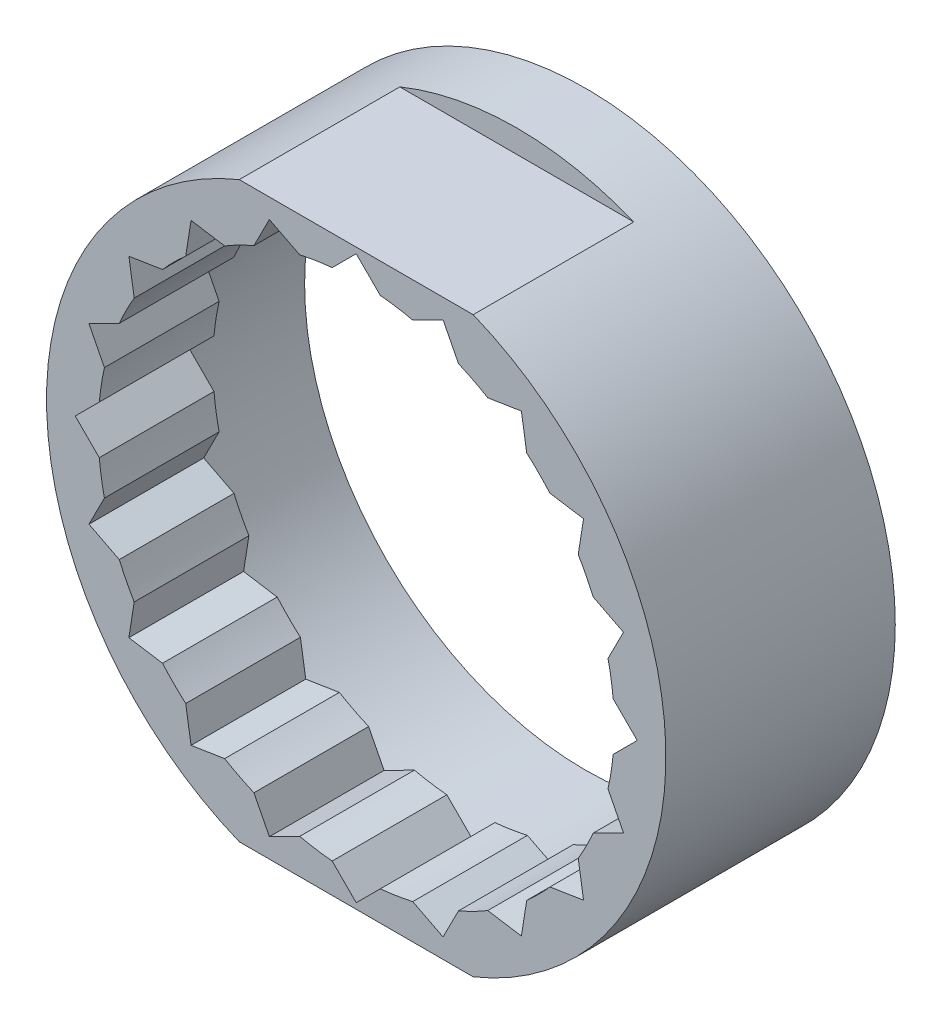
SolidWorks part; units mm, degrees
ref_plane "Front Plane" through (0, 0, 0) normal (0, 0, 1) x (1, 0, 0)
ref_plane "Top Plane" through (0, 0, 0) normal (0, 1, 0) x (1, 0, 0)
ref_plane "Right Plane" through (0, 0, 0) normal (1, 0, 0) x (0, 0, -1)
sketch "Sketch1" plane through (0, 0, 0) normal (0, 0, 1) x (1, 0, 0)
  circle A0 centre (0, 0) radius 27
extrude "Ring" add sketch "Sketch1" along normal blind 20
ref_plane "Plane_z6" through (0, 0, 6) normal (0, 0, 1) x (1, 0, 0)
sketch "Sketch2" plane through (0, 0, 6) normal (0, 0, 1) x (1, 0, 0)
  line L1 (-29, 25) -> (29, 25)
  line L2 (-29, 25) -> (-29, 29)
  line L3 (-29, 29) -> (29, 29)
  line L4 (29, 25) -> (29, 29)
  line L6 (-29, -29) -> (29, -29)
  line L7 (-29, -29) -> (-29, -25)
  line L8 (-29, -25) -> (29, -25)
  line L9 (29, -29) -> (29, -25)
extrude "Flats" cut sketch "Sketch2" along normal blind 14
sketch "Sketch3" plane through (0, 0, 0) normal (0, 0, 1) x (1, 0, 0)
  circle A0 centre (0, 0) radius 22.5
extrude "Bore" cut sketch "Sketch3" along normal blind 20
sketch "Sketch4" plane through (0, 0, 0) normal (0, 0, 1) x (1, 0, 0)
  circle A0 centre (0, 0) radius 24.5
extrude "Bore_low" cut sketch "Sketch4" along normal blind 10
ref_plane "Plane_z10" through (0, 0, 10) normal (0, 0, 1) x (1, 0, 0)
sketch "Sketch5" plane through (0, 0, 10) normal (0, 0, 1) x (1, 0, 0)
  line L0 (24.5, 0) -> (21.5, 3)
  line L1 (21.5, 3) -> (21.5, -3)
  line L2 (21.5, -3) -> (24.5, 0)
  line L3 (23.3009, 7.5709) -> (19.5207, 9.497)
  line L4 (19.5207, 9.497) -> (21.3748, 3.7907)
  line L5 (21.3748, 3.7907) -> (23.3009, 7.5709)
  line L6 (19.8209, 14.4007) -> (15.6305, 15.0644)
  line L7 (15.6305, 15.0644) -> (19.1572, 10.2103)
  line L8 (19.1572, 10.2103) -> (19.8209, 14.4007)
  line L9 (14.4007, 19.8209) -> (10.2103, 19.1572)
  line L10 (10.2103, 19.1572) -> (15.0644, 15.6305)
  line L11 (15.0644, 15.6305) -> (14.4007, 19.8209)
  line L12 (7.5709, 23.3009) -> (3.7907, 21.3748)
  line L13 (3.7907, 21.3748) -> (9.497, 19.5207)
  line L14 (9.497, 19.5207) -> (7.5709, 23.3009)
  line L15 (0, 24.5) -> (-3, 21.5)
  line L16 (-3, 21.5) -> (3, 21.5)
  line L17 (3, 21.5) -> (0, 24.5)
  line L18 (-7.5709, 23.3009) -> (-9.497, 19.5207)
  line L19 (-9.497, 19.5207) -> (-3.7907, 21.3748)
  line L20 (-3.7907, 21.3748) -> (-7.5709, 23.3009)
  line L21 (-14.4007, 19.8209) -> (-15.0644, 15.6305)
  line L22 (-15.0644, 15.6305) -> (-10.2103, 19.1572)
  line L23 (-10.2103, 19.1572) -> (-14.4007, 19.8209)
  line L24 (-19.8209, 14.4007) -> (-19.1572, 10.2103)
  line L25 (-19.1572, 10.2103) -> (-15.6305, 15.0644)
  line L26 (-15.6305, 15.0644) -> (-19.8209, 14.4007)
  line L27 (-23.3009, 7.5709) -> (-21.3748, 3.7907)
  line L28 (-21.3748, 3.7907) -> (-19.5207, 9.497)
  line L29 (-19.5207, 9.497) -> (-23.3009, 7.5709)
  line L30 (-24.5, 0) -> (-21.5, -3)
  line L31 (-21.5, -3) -> (-21.5, 3)
  line L32 (-21.5, 3) -> (-24.5, 0)
  line L33 (-23.3009, -7.5709) -> (-19.5207, -9.497)
  line L34 (-19.5207, -9.497) -> (-21.3748, -3.7907)
  line L35 (-21.3748, -3.7907) -> (-23.3009, -7.5709)
  line L36 (-19.8209, -14.4007) -> (-15.6305, -15.0644)
  line L37 (-15.6305, -15.0644) -> (-19.1572, -10.2103)
  line L38 (-19.1572, -10.2103) -> (-19.8209, -14.4007)
  line L39 (-14.4007, -19.8209) -> (-10.2103, -19.1572)
  line L40 (-10.2103, -19.1572) -> (-15.0644, -15.6305)
  line L41 (-15.0644, -15.6305) -> (-14.4007, -19.8209)
  line L42 (-7.5709, -23.3009) -> (-3.7907, -21.3748)
  line L43 (-3.7907, -21.3748) -> (-9.497, -19.5207)
  line L44 (-9.497, -19.5207) -> (-7.5709, -23.3009)
  line L45 (0, -24.5) -> (3, -21.5)
  line L46 (3, -21.5) -> (-3, -21.5)
  line L47 (-3, -21.5) -> (0, -24.5)
  line L48 (7.5709, -23.3009) -> (9.497, -19.5207)
  line L49 (9.497, -19.5207) -> (3.7907, -21.3748)
  line L50 (3.7907, -21.3748) -> (7.5709, -23.3009)
  line L51 (14.4007, -19.8209) -> (15.0644, -15.6305)
  line L52 (15.0644, -15.6305) -> (10.2103, -19.1572)
  line L53 (10.2103, -19.1572) -> (14.4007, -19.8209)
  line L54 (19.8209, -14.4007) -> (19.1572, -10.2103)
  line L55 (19.1572, -10.2103) -> (15.6305, -15.0644)
  line L56 (15.6305, -15.0644) -> (19.8209, -14.4007)
  line L57 (23.3009, -7.5709) -> (21.3748, -3.7907)
  line L58 (21.3748, -3.7907) -> (19.5207, -9.497)
  line L59 (19.5207, -9.497) -> (23.3009, -7.5709)
extrude "Teeth" cut sketch "Sketch5" along normal blind 10
